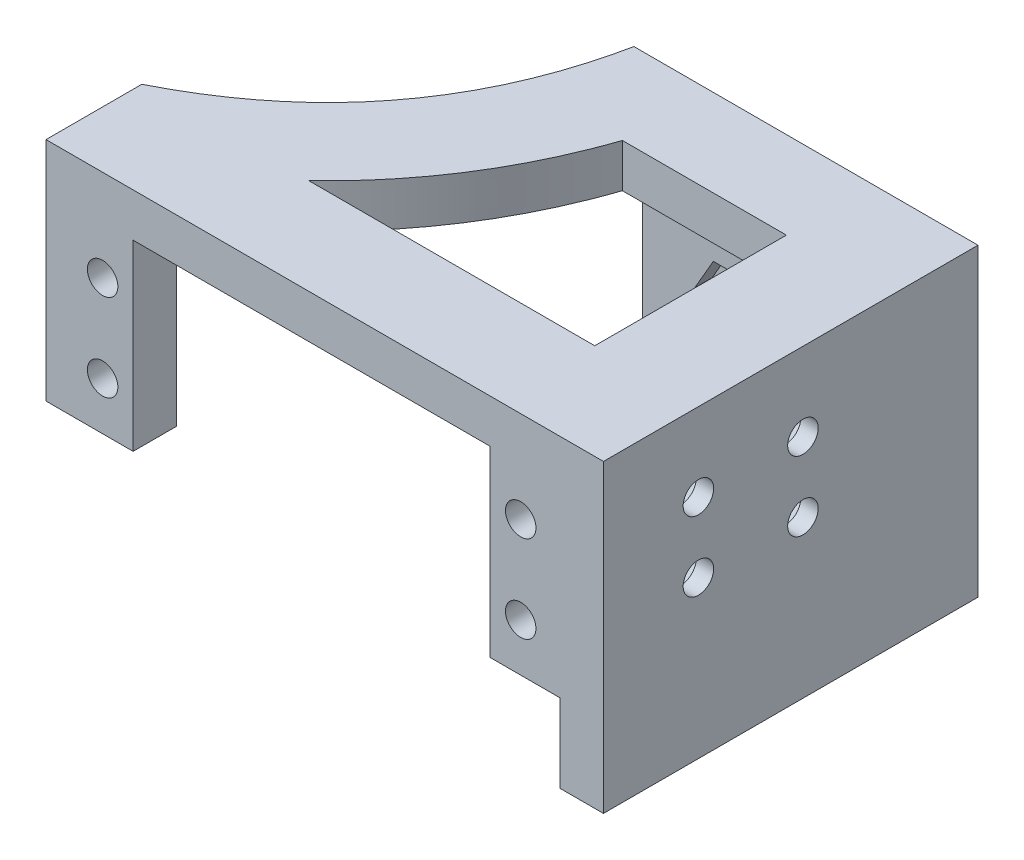
SolidWorks part; units mm, degrees
ref_plane "Front Plane" through (0, 0, 0) normal (0, 0, 1) x (1, 0, 0)
ref_plane "Top Plane" through (0, 0, 0) normal (0, 1, 0) x (1, 0, 0)
ref_plane "Right Plane" through (0, 0, 0) normal (1, 0, 0) x (0, 0, -1)
sketch "Sketch1" plane through (0, 0, 0) normal (0, 1, 0) x (1, 0, 0)
  line L1 (-5, -2.5) -> (5, -2.5)
  line L2 (-5, -2.5) -> (-5, 2.5)
  line L3 (-5, 2.5) -> (5, 2.5)
  line L4 (5, -2.5) -> (5, 2.5)
  line L5 (-5, -2.5) -> (5, 2.5) construction
  line L6 (-5, 2.5) -> (5, -2.5) construction
  line L7 (46, -2.5) -> (56, -2.5)
  line L8 (46, -2.5) -> (46, 2.5)
  line L9 (46, 2.5) -> (56, 2.5)
  line L10 (56, -2.5) -> (56, 2.5)
  line L11 (46, -2.5) -> (56, 2.5) construction
  line L12 (46, 2.5) -> (56, -2.5) construction
  point P0 (0, 0)
  point P6 (51, 0)
  dimension "D1" = 10
  dimension "D2" = 5
  dimension "D3" = 10
  dimension "D4" = 5
  dimension "D5" = 41
extrude "Boss-Extrude1" add sketch "Sketch1" along normal blind 21
sketch "Sketch2" plane through (0, 21, 0) normal (0, 1, 0) x (1, 0, 0)
  line L0 (56, 40.5) -> (-5, 40.5)
  line L1 (-5, -2.5) -> (56, -2.5)
  line L2 (56, -2.5) -> (56, 40.5)
  line L3 (-5, 40.5) -> (-5, -2.5)
  dimension "D1" = 43
extrude "Boss-Extrude2" add sketch "Sketch2" along normal blind 5
sketch "Sketch3" plane through (0, 21, 0) normal (0, -1, 0) x (1, 0, 0)
  line L0 (56, -40.5) -> (-5, -40.5) construction
  line L1 (56, -40.5) -> (25.5, -40.5)
  line L2 (56, -40.5) -> (56, -35.5)
  line L3 (56, -35.5) -> (25.5, -35.5)
  line L4 (25.5, -40.5) -> (25.5, -35.5)
  line L6 (56, -2.5) -> (56, -40.5) construction
  dimension "D1" = 5
  dimension "D3" = 30.5
extrude "Boss-Extrude3" add sketch "Sketch3" along normal blind 21
sketch "Sketch4" plane through (0, 0, -35.5) normal (0, 0, 1) x (1, 0, 0)
  line L0 (25.5, 0) -> (25.5, 21) construction
  line L1 (56, 21) -> (25.5, 21) construction
  circle A0 centre (35.75, 10.5) radius 2.2
  dimension "D1" = 4.4
  dimension "D2" = 10.25
  dimension "D3" = 10.5
extrude "Cut-Extrude1" cut sketch "Sketch4" against normal up to next
sketch "Sketch5" plane through (0, 0, 2.5) normal (0, 0, 1) x (1, 0, 0)
  line L0 (5, 21) -> (5, 0) construction
  line L1 (5, 10.5) -> (0.9353, 10.5) construction
  circle A0 centre (1.5, 15.5) radius 1.75
  circle A1 centre (49.5, 15.5) radius 1.75
  circle A2 centre (49.5, 5.5) radius 1.75
  circle A3 centre (1.5, 5.5) radius 1.75
  dimension "D1" = 3.5
  dimension "D2" = 3.5
  dimension "D3" = 5
  dimension "D4" = 2
  dimension "D5" = 2
extrude "Cut-Extrude2" cut sketch "Sketch5" against normal up to next
sketch "Sketch7" plane through (0, 21, 0) normal (0, -1, 0) x (1, 0, 0)
  line L0 (-5, -40.5) -> (-5, -2.5) construction
  line L1 (25.5, -40.5) -> (-5, -40.5) construction
  line L2 (-5, -8.5) -> (-5, -40.5)
  line L3 (-5, -40.5) -> (19.5, -40.5)
  line L4 (-16, -51.5) -> (32.9728, -51.5)
  line L5 (-16, 9.2992) -> (-16, -51.5)
  line L6 (47, -8.5) -> (47, -31.9724)
  line L8 (5, -8.5) -> (46, -8.5)
  line L9 (5, -8.5) -> (47, -8.5)
  line L19 (56, -2.5) -> (56, -35.5) construction
  line L20 (47, -30.5) -> (16.3931, -30.5)
  line L21 (25.5, -40.5) -> (56, -40.5) construction
  spline S0 degree 2 poles (-5, -8.5) (15.0094, -18.5057) (19.5, -40.5) knots 0 0 0 1 1 1
  spline S1 degree 1 poles (-16, 9.2992) (32.9728, -51.5) knots 0 0 1 1 construction
  spline S2 degree 3 poles (-16, 9.2992) (-14.5844, 8.5913) (-11.7534, 7.1757) (-7.5059, 5.0517) (-4.3231, 3.4602) (-2.1967, 2.3968) (-1.3175, 1.9573) (-0.5983, 1.5974) (-0.1025, 1.3503) (0.5663, 1.0125) (1.3892, 0.584) (2.4265, 0.0235) (4.047, -0.8991) (6.0248, -2.1137) (8.3103, -3.6663) (11.2387, -5.865) (14.6658, -8.8536) (18.3744, -12.8147) (21.65, -17.1296) (24.471, -21.7688) (26.4339, -25.8772) (27.7713, -29.2934) (28.6591, -31.9169) (29.3037, -34.1514) (29.7635, -35.9676) (30.0271, -37.1122) (30.2005, -37.923) (30.2946, -38.3822) (30.3704, -38.754) (30.4714, -39.2486) (30.7088, -40.411) (31.2259, -42.9441) (32.0196, -46.8313) (32.6551, -49.944) (32.9728, -51.5) knots -0.397806 -0.397806 -0.397806 -0.397806 -0.291687 -0.185569 -0.07945 -0.052921 -0.026391 -0.013126 0.000138 0.013403 0.026668 0.053198 0.079727 0.132786 0.185846 0.238905 0.345023 0.451142 0.55726 0.663378 0.769497 0.822556 0.875615 0.928674 0.955204 0.981733 0.994998 1.001631 1.008263 1.021528 1.034793 1.087852 1.19397 1.300089 1.300089 1.300089 1.300089
  line M14 (-5, -2.5) -> (-5, -40.5)
  line M15 (-5, -40.5) -> (25.5, -40.5)
  dimension "D1" = 6
  dimension "D2" = 6
  dimension "D5" = 9
  dimension "D6" = 10
  dimension "D3" = 11
  dimension "D4" = 11
extrude "Cut-Extrude4" cut sketch "Sketch7" against normal up to next contours S0 M14 M15 | L9 S2 L20 L6
sketch "Sketch10" plane through (56, 0, 0) normal (1, 0, 0) x (0, 0, -1)
  line L0 (40.5, 26) -> (40.5, 0) construction
  line L1 (-2.5, 26) -> (40.5, 26)
  line L2 (-2.5, 26) -> (-2.5, -9)
  line L3 (-2.5, -9) -> (40.5, -9)
  line L4 (40.5, 26) -> (40.5, -9)
  dimension "D1" = 35
extrude "Boss-Extrude4" add sketch "Sketch10" along normal blind 3 and the other way blind 2
sketch "Sketch11" plane through (0, 0, -35.5) normal (0, 0, 1) x (1, 0, 0)
  line L1 (37.8862, 14.2) -> (33.6138, 14.2)
  line L2 (33.6138, 14.2) -> (31.4776, 10.5)
  line L3 (31.4776, 10.5) -> (33.6138, 6.8)
  line L4 (33.6138, 6.8) -> (37.8862, 6.8)
  line L5 (37.8862, 6.8) -> (40.0224, 10.5)
  line L6 (40.0224, 10.5) -> (37.8862, 14.2)
  line L8 (5, 21) -> (46, 21) construction
  circle A0 centre (35.75, 10.5) radius 3.7 construction
  dimension "D1" = 7.4
extrude "Cut-Extrude5" cut sketch "Sketch11" against normal blind 2
sketch "Sketch12" plane through (59, 0, 0) normal (1, 0, 0) x (0, 0, -1)
  line L0 (40.5, 26) -> (-2.5, 26) construction
  line L1 (-2.5, 26) -> (-2.5, -9) construction
  circle A0 centre (8.4, 17) radius 1.75
  circle A1 centre (8.4, 9) radius 1.75
  circle A2 centre (20.4, 17) radius 1.75
  circle A3 centre (20.4, 9) radius 1.75
  dimension "D1" = 3.5
  dimension "D2" = 3.5
  dimension "D4" = 10.9
  dimension "D7" = 3.5
  dimension "D8" = 3.5
  dimension "D3" = 9
  dimension "D5" = 12
  dimension "D6" = 8
extrude "Cut-Extrude6" cut sketch "Sketch12" against normal up to next
sketch "Sketch13" plane through (54, 0, 0) normal (-1, 0, 0) x (0, 0, 1)
  line L0 (-2.5, 21) -> (-35.5, 21) construction
  line L1 (-12.095, 17) -> (-10.2475, 13.8)
  line L2 (-10.2475, 13.8) -> (-6.5525, 13.8)
  line L3 (-6.5525, 13.8) -> (-4.705, 17)
  line L4 (-4.705, 17) -> (-6.5525, 20.2)
  line L5 (-6.5525, 20.2) -> (-10.2475, 20.2)
  line L6 (-10.2475, 20.2) -> (-12.095, 17)
  line L7 (-10.2475, 5.8) -> (-6.5525, 5.8)
  line L8 (-6.5525, 5.8) -> (-4.705, 9)
  line L9 (-4.705, 9) -> (-6.5525, 12.2)
  line L10 (-6.5525, 12.2) -> (-10.2475, 12.2)
  line L11 (-10.2475, 12.2) -> (-12.095, 9)
  line L12 (-12.095, 9) -> (-10.2475, 5.8)
  line L13 (-40.5, 21) -> (-8.5, 21) construction
  line L14 (-18.5525, 20.2) -> (-22.2475, 20.2)
  line L15 (-22.2475, 20.2) -> (-24.095, 17)
  line L16 (-24.095, 17) -> (-22.2475, 13.8)
  line L17 (-22.2475, 13.8) -> (-18.5525, 13.8)
  line L18 (-18.5525, 13.8) -> (-16.705, 17)
  line L19 (-16.705, 17) -> (-18.5525, 20.2)
  line L20 (-22.2475, 12.2) -> (-24.095, 9)
  line L21 (-24.095, 9) -> (-22.2475, 5.8)
  line L22 (-22.2475, 5.8) -> (-18.5525, 5.8)
  line L23 (-18.5525, 5.8) -> (-16.705, 9)
  line L24 (-16.705, 9) -> (-18.5525, 12.2)
  line L25 (-18.5525, 12.2) -> (-22.2475, 12.2)
  circle A0 centre (-8.4, 17) radius 3.2 construction
  circle A1 centre (-8.4, 9) radius 3.2 construction
  circle A2 centre (-20.4, 17) radius 3.2 construction
  circle A3 centre (-20.4, 9) radius 3.2 construction
  dimension "D1" = 6.4
  dimension "D2" = 6.4
  dimension "D3" = 6.4
  dimension "D4" = 6.4
extrude "Cut-Extrude7" cut sketch "Sketch13" against normal blind 3 contours L14 L15 L16 L17 L18 L19
